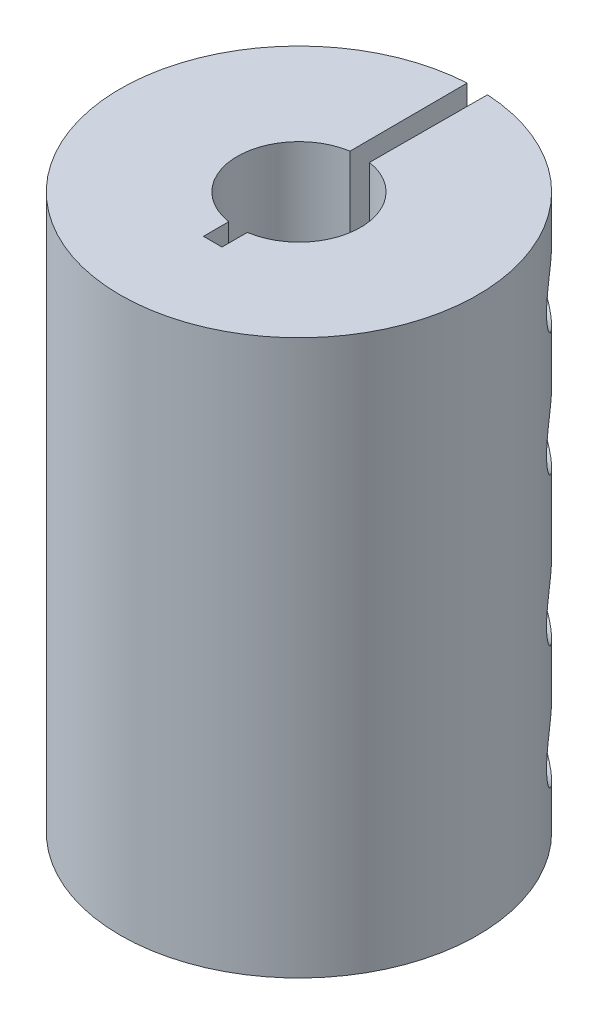
SolidWorks part; units mm, degrees
material "3.3547 (EN-AW 5083)"
ref_plane "Front Plane" through (0, 0, 0) normal (0, 0, 1) x (1, 0, 0)
ref_plane "Top Plane" through (0, 0, 0) normal (0, 1, 0) x (1, 0, 0)
ref_plane "Right Plane" through (0, 0, 0) normal (1, 0, 0) x (0, 0, -1)
sketch "Sketch1" plane through (0, 0, 0) normal (0, 1, 0) x (1, 0, 0)
  circle A0 centre (0, 0) radius 5
  circle A1 centre (0, 0) radius 14.5
  dimension "D1" = 10
  dimension "D2" = 29
extrude "Boss-Extrude1" add sketch "Sketch1" along normal mid plane 45
sketch "Sketch2" plane through (0, -22.5, 0) normal (0, -1, 0) x (1, 0, 0)
  line L0 (-0.75, 7) -> (-0.825, -14.4765) construction
  line L1 (0.75, 7) -> (0.825, -14.4765) construction
  line L2 (0, -44.7868) -> (0, 44.7868) construction
  line L3 (-0.825, -14.4765) -> (-0.75, 7)
  line L4 (0.75, 7) -> (0.825, -14.4765)
  line L5 (-0.75, 7) -> (0.75, 7)
  circle A0 centre (0, 0) radius 14.5 construction
  arc A2 (-0.825, -14.4765) -> (0.825, -14.4765) centre (0, 0) ccw
  point P8 (0, 7)
  dimension "D3" = 7
  dimension "D1" = 0.2
  dimension "D2" = 0.2
  dimension "D4" = 1.5
extrude "Cut-Extrude1" cut sketch "Sketch2" against normal up to next
ref_plane "Plane1" through (14.5, 0, 0) normal (1, 0, 0) x (0, 0, -1)
sketch "Sketch3" plane through (14.5, 0, 0) normal (1, 0, 0) x (0, 0, -1)
  line L0 (55, 0) -> (-55, 0) construction
  line L1 (0, 44.2539) -> (0, -44.2539) construction
  circle A0 centre (11, 16) radius 2
  circle A1 centre (11, 6) radius 2
  circle A2 centre (11, -6) radius 2
  circle A3 centre (11, -16) radius 2
  dimension "D1" = 4
  dimension "D2" = 10
  dimension "D3" = 10
  dimension "D4" = 6
  dimension "D5" = 6
  dimension "D6" = 11
extrude "Cut-Extrude2" cut sketch "Sketch3" against normal through all
sketch "Sketch4" plane through (14.5, 0, 0) normal (1, 0, 0) x (0, 0, -1)
  circle A0 centre (11, 16) radius 3
  circle A1 centre (11, 6) radius 3
  circle A2 centre (11, -6) radius 3
  circle A3 centre (11, -16) radius 3
  dimension "D1" = 6
extrude "Cut-Extrude3" cut sketch "Sketch4" against normal blind 10.5
